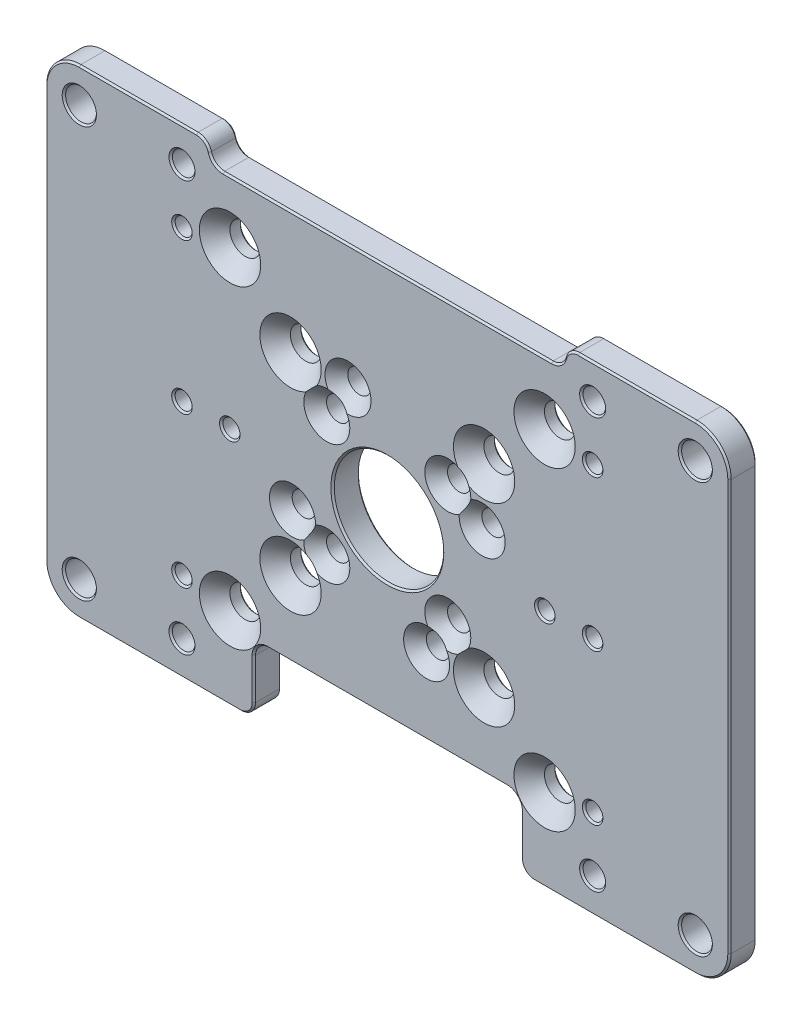
SolidWorks part; units mm, degrees
ref_plane "Front Plane" through (0, 0, 0) normal (0, 0, 1) x (1, 0, 0)
ref_plane "Top Plane" through (0, 0, 0) normal (0, 1, 0) x (1, 0, 0)
ref_plane "Right Plane" through (0, 0, 0) normal (1, 0, 0) x (0, 0, -1)
sketch "Sketch1" plane through (0, 0, 0) normal (0, 0, 1) x (1, 0, 0)
  line L0 (50, 35) -> (-50, 35)
  line L1 (-50, 35) -> (-50, -35)
  line L2 (-50, -35) -> (50, -35)
  line L3 (50, -35) -> (50, 35)
extrude "Boss-Extrude1" add sketch "Sketch1" against normal blind 4
sketch "Sketch2" plane through (0, 0, -4) normal (0, 0, -1) x (-1, 0, 0)
  line L0 (27.873, 35) -> (-27.873, 35)
  line L1 (-24, 32) -> (24, 32)
  arc A0 (-27.873, 35) -> (-25.9365, 33.5) centre (-27.873, 33) cw
  arc A1 (-25.9365, 33.5) -> (-24, 32) centre (-24, 34) ccw
  arc A2 (24, 32) -> (25.9365, 33.5) centre (24, 34) ccw
  arc A3 (25.9365, 33.5) -> (27.873, 35) centre (27.873, 33) cw
extrude "Cut-Extrude1" cut sketch "Sketch2" against normal through all
sketch "Sketch3" plane through (0, 0, -4) normal (0, 0, -1) x (-1, 0, 0)
  line L0 (-19.5, -35) -> (19.5, -35)
  line L1 (19.5, -35) -> (19.5, -27)
  line L2 (17.5, -25) -> (-17.5, -25)
  line L3 (-19.5, -27) -> (-19.5, -35)
  arc A0 (19.5, -27) -> (17.5, -25) centre (17.5, -27) ccw
  arc A1 (-17.5, -25) -> (-19.5, -27) centre (-17.5, -27) ccw
extrude "Cut-Extrude2" cut sketch "Sketch3" against normal through all
hole_wizard "Ø2.5 (2.5) Diameter Hole1" positions "Sketch5" profile "Sketch4" hole size "Ø2.5" standard "ANSI Metric"
sketch "Sketch5" plane through (0, 0, -4) normal (0, 0, -1) x (-1, 0, 0)
  point P0 (-30, 22)
sketch "Sketch4" plane through (30, 22, -4) normal (1, 0, 0) x (0, 1, 0)
  line L0 (0, 0) -> (0, 4)
  line L1 (0, 4) -> (1.25, 4)
  line L2 (1.25, 4) -> (1.25, 0)
  line L5 (1.25, 0) -> (0, 0)
  line L11 (0, -6.35) -> (0, 107.95) construction
  dimension "Thru Hole Dia." = 2.5
  dimension "Thru Hole Depth" = 4
hole_wizard "Ø2.5 (2.5) Diameter Hole2" positions "Sketch7" profile "Sketch6" hole size "Ø2.5" standard "ANSI Metric"
sketch "Sketch7" plane through (0, 0, 0) normal (0, 0, 1) x (1, 0, 0)
  point P0 (23.0125, 0)
  point P1 (-23.0125, 0)
  point P2 (-30, 22)
  point P3 (30, 0)
  point P4 (30, -22)
  point P5 (-30, -22)
  point P6 (-30, 0)
sketch "Sketch6" plane through (23.0125, 0, 0) normal (1, 0, 0) x (0, -1, 0)
  line L0 (0, 0) -> (0, 4)
  line L1 (0, 4) -> (1.25, 4)
  line L2 (1.25, 4) -> (1.25, 0)
  line L5 (1.25, 0) -> (0, 0)
  line L11 (0, -6.35) -> (0, 107.95) construction
  dimension "Thru Hole Dia." = 2.5
  dimension "Thru Hole Depth" = 4
hole_wizard "Ø4.5 (4.5) Diameter Hole1" positions "Sketch9" profile "Sketch8" hole size "Ø4.5" standard "ANSI Metric"
sketch "Sketch9" plane through (0, 0, 0) normal (0, 0, 1) x (1, 0, 0)
  point P0 (-45, 30)
  point P1 (45, -30)
sketch "Sketch8" plane through (-45, 30, 0) normal (1, 0, 0) x (0, -1, 0)
  line L0 (0, 0) -> (0, 4)
  line L1 (0, 4) -> (2.25, 4)
  line L2 (2.25, 4) -> (2.25, 0)
  line L5 (2.25, 0) -> (0, 0)
  line L11 (0, -6.35) -> (0, 107.95) construction
  dimension "Thru Hole Dia." = 4.5
  dimension "Thru Hole Depth" = 4
hole_wizard "Ø4.5 (4.5) Diameter Hole2" positions "Sketch11" profile "Sketch10" hole size "Ø4.5" standard "ANSI Metric"
sketch "Sketch11" plane through (0, 0, -4) normal (0, 0, -1) x (-1, 0, 0)
  point P0 (45, -30)
  point P1 (-45, 30)
sketch "Sketch10" plane through (-45, -30, -4) normal (1, 0, 0) x (0, 1, 0)
  line L0 (0, 0) -> (0, 4)
  line L1 (0, 4) -> (2.25, 4)
  line L2 (2.25, 4) -> (2.25, 0)
  line L5 (2.25, 0) -> (0, 0)
  line L11 (0, -6.35) -> (0, 107.95) construction
  dimension "Thru Hole Dia." = 4.5
  dimension "Thru Hole Depth" = 4
hole_wizard "Ø3.3 (3.3) Diameter Hole1" positions "Sketch13" profile "Sketch12" hole size "Ø3.3" standard "ANSI Metric"
sketch "Sketch13" plane through (0, 0, -4) normal (0, 0, -1) x (-1, 0, 0)
  point P0 (-30, -30)
sketch "Sketch12" plane through (30, -30, -4) normal (1, 0, 0) x (0, 1, 0)
  line L0 (0, 0) -> (0, 4)
  line L1 (0, 4) -> (1.65, 4)
  line L2 (1.65, 4) -> (1.65, 0)
  line L5 (1.65, 0) -> (0, 0)
  line L11 (0, -6.35) -> (0, 107.95) construction
  dimension "Thru Hole Dia." = 3.3
  dimension "Thru Hole Depth" = 4
hole_wizard "Ø3.3 (3.3) Diameter Hole2" positions "Sketch15" profile "Sketch14" hole size "Ø3.3" standard "ANSI Metric"
sketch "Sketch15" plane through (0, 0, 0) normal (0, 0, 1) x (1, 0, 0)
  point P0 (-30, 30)
  point P1 (-30, -30)
  point P2 (30, 30)
sketch "Sketch14" plane through (-30, 30, 0) normal (1, 0, 0) x (0, -1, 0)
  line L0 (0, 0) -> (0, 4)
  line L1 (0, 4) -> (1.65, 4)
  line L2 (1.65, 4) -> (1.65, 0)
  line L5 (1.65, 0) -> (0, 0)
  line L11 (0, -6.35) -> (0, 107.95) construction
  dimension "Thru Hole Dia." = 3.3
  dimension "Thru Hole Depth" = 4
hole_wizard "Ø16.0 (16) Diameter Hole1" positions "Sketch17" profile "Sketch16" hole size "Ø16.0" standard "ANSI Metric"
sketch "Sketch17" plane through (0, 0, 0) normal (0, 0, 1) x (1, 0, 0)
  point P0 (0, 0)
sketch "Sketch16" plane through (0, 0, 0) normal (1, 0, 0) x (0, -1, 0)
  line L0 (0, 0) -> (0, 4)
  line L1 (0, 4) -> (8, 4)
  line L2 (8, 4) -> (8, 0)
  line L5 (8, 0) -> (0, 0)
  line L11 (0, -6.35) -> (0, 107.95) construction
  dimension "Thru Hole Dia." = 16
  dimension "Thru Hole Depth" = 4
hole_wizard "CSK for M3 Flat Head Machine Screw1" positions "Sketch19" profile "Sketch18" countersink size "M3" standard "ANSI Metric"
sketch "Sketch19" plane through (0, 0, 0) normal (0, 0, 1) x (1, 0, 0)
  point P0 (-8.8388, -8.8388)
  point P1 (-13.8582, -5.7403)
  point P2 (-8.8388, 8.8388)
  point P3 (-5.7403, 13.8582)
  point P4 (8.8388, 8.8388)
  point P5 (13.8582, 5.7403)
  point P6 (8.8388, -8.8388)
  point P7 (5.7403, -13.8582)
sketch "Sketch18" plane through (-8.8388, -8.8388, 0) normal (1, 0, 0) x (0, -1, 0)
  line L0 (0, 0) -> (0, 4)
  line L1 (0, 4) -> (1.7, 4)
  line L2 (1.7, 4) -> (1.7, 1.66)
  line L3 (1.7, 1.66) -> (3.36, 0)
  line L5 (3.36, 0) -> (0, 0)
  line L6 (-1.7, 1.66) -> (-3.36, 0) construction
  line L11 (0, -6.35) -> (0, 107.95) construction
  dimension "Thru Hole Dia." = 3.4
  dimension "Thru Hole Depth" = 4
  dimension "Near C'Sink Dia." = 6.72
  dimension "Near C'Sink Angle" = 90
hole_wizard "CSK for M4 Flat Head Machine Screw1" positions "Sketch21" profile "Sketch20" countersink size "M4" standard "ANSI Metric"
sketch "Sketch21" plane through (0, 0, 0) normal (0, 0, 1) x (1, 0, 0)
  point P0 (-14.1421, -14.1421)
  point P1 (-22.981, -22.981)
  point P2 (-14.1421, 14.1421)
  point P3 (-22.981, 22.981)
  point P4 (14.1421, 14.1421)
  point P5 (22.981, 22.981)
  point P6 (14.1421, -14.1421)
  point P7 (22.981, -22.981)
sketch "Sketch20" plane through (-14.1421, -14.1421, 0) normal (1, 0, 0) x (0, -1, 0)
  line L0 (0, 0) -> (0, 4)
  line L1 (0, 4) -> (2.25, 4)
  line L2 (2.25, 4) -> (2.25, 2.23)
  line L3 (2.25, 2.23) -> (4.48, 0)
  line L5 (4.48, 0) -> (0, 0)
  line L6 (-2.25, 2.23) -> (-4.48, 0) construction
  line L11 (0, -6.35) -> (0, 107.95) construction
  dimension "Thru Hole Dia." = 4.5
  dimension "Thru Hole Depth" = 4
  dimension "Near C'Sink Dia." = 8.96
  dimension "Near C'Sink Angle" = 90
fillet "Fillet1" radius 2 2 edges at (19.5, -35, -2) (-19.5, -35, -2)
fillet "Fillet2" radius 5 4 edges at (50, 35, -2) (50, -35, -2) (-50, 35, -2) (-50, -35, -2)
chamfer "Chamfer1" distance 0.25 angle 45 94 edges at (31.25, -22, -4) (-12.1582, -5.7403, -4) (50, 0, 0) (48.5355, -33.5355, 0) (48.5355, 33.5355, 0) (33.25, -35, 0) (36.4365, 35, 0) (20.0858, -34.4142, 0) (26.6482, 34.5811, 0) (19.5, -30, 0) (25.2247, 32.4189, 0) (18.9142, -25.5858, 0) (0, 32, 0) (0, -25, 0) (-25.2247, 32.4189, 0) (-18.9142, -25.5858, 0) (-26.6482, 34.5811, 0) (-19.5, -30, 0) (-36.4365, 35, 0) (-20.0858, -34.4142, 0) (-48.5355, 33.5355, 0) (-33.25, -35, 0) (-50, 0, 0) (-48.5355, -33.5355, 0) (-33.25, -35, -4) (-48.5355, -33.5355, -4) (-20.0858, -34.4142, -4) (-50, 0, -4) (-19.5, -30, -4) (-48.5355, 33.5355, -4) (-18.9142, -25.5858, -4) (-36.4365, 35, -4) (0, -25, -4) (-26.6482, 34.5811, -4) (18.9142, -25.5858, -4) (-25.2247, 32.4189, -4) (19.5, -30, -4) (0, 32, -4) (20.0858, -34.4142, -4) (25.2247, 32.4189, -4) (33.25, -35, -4) (26.6482, 34.5811, -4) (48.5355, -33.5355, -4) (36.4365, 35, -4) (50, 0, -4) (48.5355, 33.5355, -4) (-42.75, 30, -4) (15.5582, 5.7403, -4) (24.2625, 0, -4) (-28.35, -30, -4) (-4.0403, 13.8582, -4) (7.4403, -13.8582, -4) (31.25, 0, -4) (-28.75, 0, -4) (47.25, -30, -4) (31.65, 30, -4) (-11.8921, -14.1421, -4) (-11.8921, 14.1421, -4) (16.3921, 14.1421, -4) (16.3921, -14.1421, -4) (8, 0, -4) (8, 0, 0) (47.25, -30, 0) (42.75, 30, 0) (31.65, 30, 0) (28.75, 22, 0) (24.2625, 0, 0) (31.25, 0, 0) (31.25, -22, 0) (28.75, 22, -4) (28.35, -30, 0) (-28.75, -22, -4) (-47.25, -30, 0) (-28.75, 22, -4) (-28.35, -30, 0) (-21.7625, 0, -4) (-28.75, -22, 0) (42.75, 30, -4) (-21.7625, 0, 0) (-47.25, -30, -4) (-28.75, 0, 0) (28.35, -30, -4) (-28.75, 22, 0) (-28.35, 30, -4) (-28.35, 30, 0) (-20.731, -22.981, -4) (-42.75, 30, 0) (-7.1388, -8.8388, -4) (-20.731, 22.981, -4) (-7.1388, 8.8388, -4) (25.231, 22.981, -4) (10.5388, 8.8388, -4) (25.231, -22.981, -4) (10.5388, -8.8388, -4)
